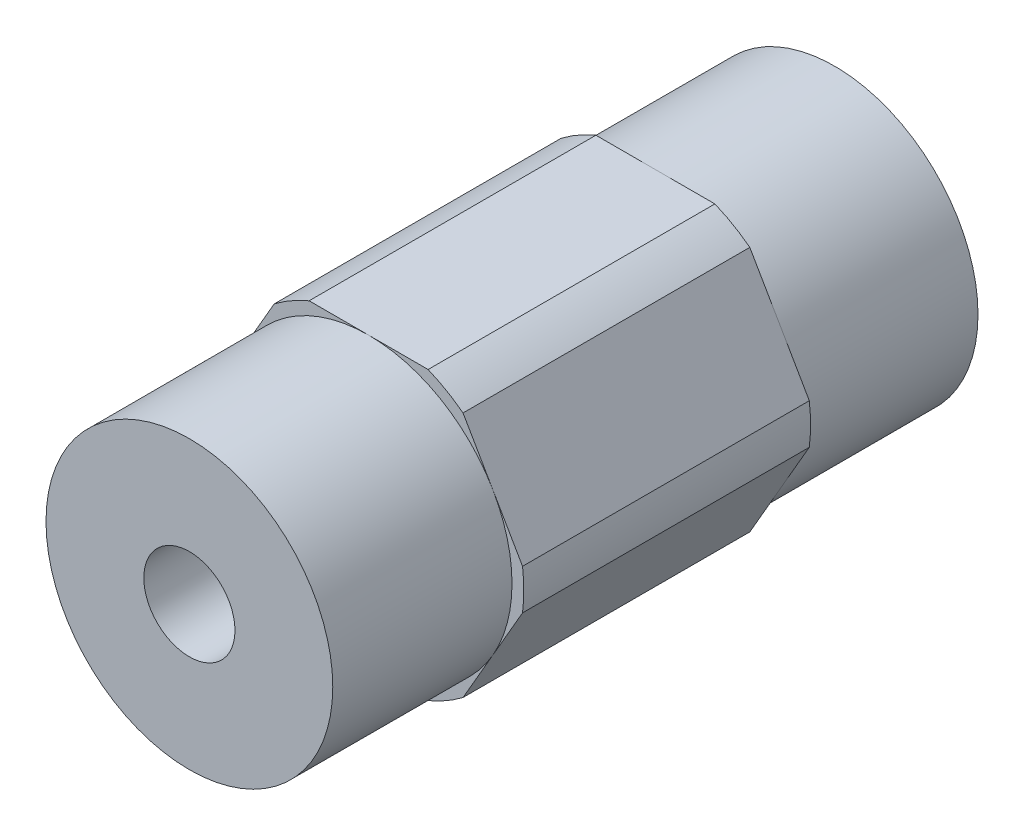
SolidWorks part; units mm, degrees
material "7075-T6 (SN)"
ref_plane "Front Plane" through (0, 0, 0) normal (0, 0, 1) x (1, 0, 0)
ref_plane "Top Plane" through (0, 0, 0) normal (0, 1, 0) x (1, 0, 0)
ref_plane "Right Plane" through (0, 0, 0) normal (1, 0, 0) x (0, 0, -1)
sketch "Sketch1" plane through (0, 0, 0) normal (0, 0, 1) x (1, 0, 0)
  line L1 (7.3323, 0) -> (3.6662, 6.35)
  line L2 (3.6662, 6.35) -> (-3.6662, 6.35)
  line L3 (-3.6662, 6.35) -> (-7.3323, 0)
  line L4 (-7.3323, 0) -> (-3.6662, -6.35)
  line L5 (-3.6662, -6.35) -> (3.6662, -6.35)
  line L6 (3.6662, -6.35) -> (7.3323, 0)
  circle A0 centre (0, 0) radius 6.35 construction
  circle A1 centre (0, 0) radius 2.0193
  circle A2 centre (0, 0) radius 6.875
  dimension "D1" = 12.7
  dimension "D2" = 4.0386
  dimension "D3" = 13.75
extrude "Boss-Extrude1" add sketch "Sketch1" along normal mid plane 28.575 contours L1 A2 L2 L3 L4 L5 L6 A1
hole_wizard "#10-32 Tapped Hole1" positions "3DSketch1" profile "Sketch3" tap size "#10-32" standard "ANSI Inch"
sketch3d "3DSketch1"
  circle A0 centre (0, 0, -14.2875) radius 2.0193 construction
  circle A1 centre (0, 0, 14.2875) radius 2.0193 construction
  point P0 (0, 0, 14.2875)
  point P2 (0, 0, -14.2875)
  point P6 (0, 0, -12.2682)
  point P9 (0, 0, 16.3068)
sketch "Sketch3" plane through (0, 0, 14.2875) normal (1, 0, 0) x (0, -1, 0)
  line L0 (0, 0) -> (0, 13.1513)
  line L1 (0, 13.1513) -> (2.0193, 11.938)
  line L2 (2.0193, 11.938) -> (2.0193, 0)
  line L5 (2.0193, 0) -> (0, 0)
  line L10 (0, 13.1513) -> (-2.0193, 11.938) construction
  line L11 (0, -6.35) -> (0, 107.95) construction
  dimension "Tap Drill Dia." = 4.0386
  dimension "Tap Drill Depth" = 11.938
  dimension "Drill Angle" = 118
cosmetic thread "Hole Thread1" parameters "D1"=9.652, "D2"=4.826
cosmetic thread "Hole Thread2" parameters "D1"=9.652, "D2"=4.826
sketch "Sketch4" plane through (0, 0, 14.2875) normal (0, 0, 1) x (1, 0, 0)
  circle A0 centre (0, 0) radius 6.35
  dimension "D1" = 12.7
extrude "Cut-Extrude-Thin1" cut sketch "Sketch4" against normal blind 7.9375 thin
mirror "Mirror1" about plane through (0, 0, 0) normal (0, 0, 1) of "Cut-Extrude-Thin1"
equation "\"D3@Sketch1\"=13.75mm"
